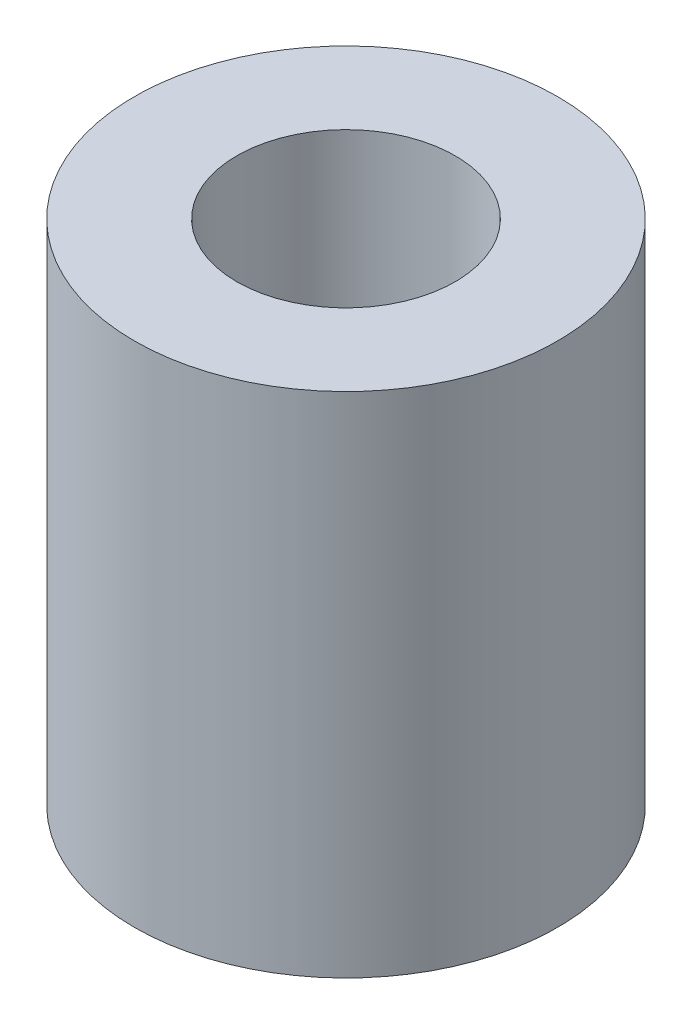
SolidWorks part; units mm, degrees
material "ABS"
ref_plane "Front Plane" through (0, 0, 0) normal (0, 0, 1) x (1, 0, 0)
ref_plane "Top Plane" through (0, 0, 0) normal (0, 1, 0) x (1, 0, 0)
ref_plane "Right Plane" through (0, 0, 0) normal (1, 0, 0) x (0, 0, -1)
sketch "Sketch1" plane through (0, 0, 0) normal (0, 1, 0) x (1, 0, 0)
  circle A0 centre (0, 0) radius 3.175
  dimension "D1" = 6.35
extrude "Boss-Extrude1" add sketch "Sketch1" along normal blind 7.62
sketch "Sketch4" plane through (0, 7.62, 0) normal (0, 1, 0) x (1, 0, 0)
  circle A0 centre (0, 0) radius 1.6383
  dimension "D1" = 3.2766
extrude "Cut-Extrude1" cut sketch "Sketch4" against normal blind 5.08
